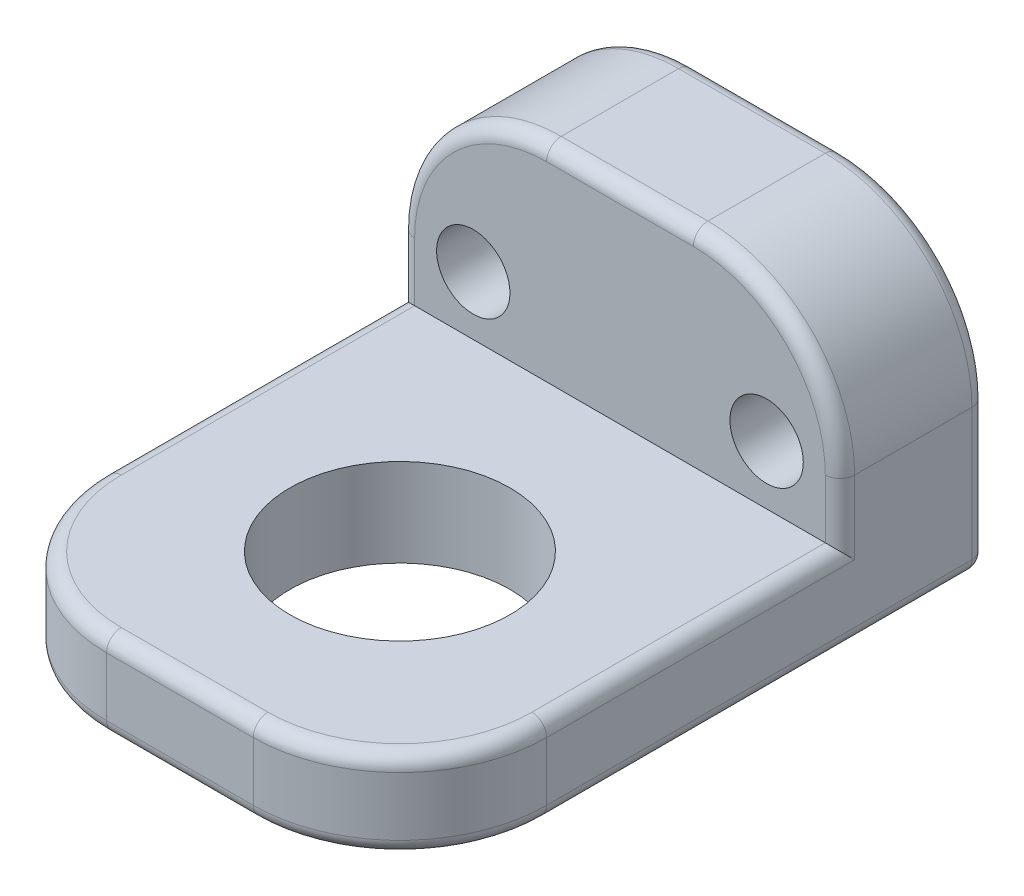
SolidWorks part; units mm, degrees
ref_plane "前视基准面" through (0, 0, 0) normal (0, 0, 1) x (1, 0, 0)
ref_plane "上视基准面" through (0, 0, 0) normal (0, 1, 0) x (1, 0, 0)
ref_plane "右视基准面" through (0, 0, 0) normal (1, 0, 0) x (0, 0, -1)
sketch "草图1" plane through (0, 0, 0) normal (0, 0, 1) x (1, 0, 0)
  line L1 (-15, 10) -> (15, 10)
  line L2 (-15, 10) -> (-15, -10)
  line L3 (-15, -10) -> (15, -10)
  line L4 (15, 10) -> (15, -10)
  line L5 (-15, 10) -> (15, -10) construction
  line L6 (-15, -10) -> (15, 10) construction
  point P0 (0, 0)
  dimension "D1" = 30
  dimension "D2" = 20
extrude "凸台-拉伸1" add sketch "草图1" along normal blind 10
sketch "草图2" plane through (0, 0, 10) normal (0, 0, 1) x (1, 0, 0)
  line L0 (-18.2315, 0) -> (18.886, 0) construction
  circle A0 centre (-10, 0) radius 2.5
  circle A1 centre (10, 0) radius 2.5
  dimension "D1" = 5
  dimension "D2" = 20
  dimension "D3" = 10
extrude "切除-拉伸1" cut sketch "草图2" against normal through all
sketch "草图3" plane through (0, 0, 10) normal (0, 0, 1) x (1, 0, 0)
  line L0 (-15, -10) -> (15, -10) construction
  line L2 (15, -10) -> (15, -4)
  line L3 (15, -4) -> (-15, -4)
  line L4 (-15, -10) -> (-15, -4)
  line L5 (0, -10) -> (-15, -4) construction
  line L6 (15, -4) -> (0, -10) construction
  line L7 (-15, 10) -> (-15, -10) construction
  line L8 (-15, -10) -> (15, -10)
  point P0 (0, -10)
  dimension "D1" = 6
extrude "凸台-拉伸2" add sketch "草图3" along normal blind 30
sketch "草图4" plane through (0, -10, 0) normal (0, -1, 0) x (1, 0, 0)
  line L0 (-15, 40) -> (15, 40) construction
  circle A0 centre (0, 25) radius 7.5
  dimension "D1" = 15
  dimension "D2" = 15
extrude "切除-拉伸2" cut sketch "草图4" against normal blind 30
fillet "圆角1" radius 10 2 edges at (-15, -7, 40) (15, -7, 40)
fillet "圆角2" radius 10 2 edges at (15, 10, 5) (-15, 10, 5)
fillet "圆角3" radius 1 11 edges at (15, -5, 0) (12.0711, 7.0711, 0) (0, 10, 0) (-12.0711, 7.0711, 0) (15, -10, 15) (12.0711, -10, 37.0711) (0, -10, 40) (-12.0711, -10, 37.0711) (-15, -5, 0) (0, -10, 0) (-15, -10, 15)
fillet "圆角4" radius 1 10 edges at (15, -4, 20) (12.0711, -4, 37.0711) (0, -4, 40) (-12.0711, -4, 37.0711) (15, -2, 10) (12.0711, 7.0711, 10) (0, 10, 10) (-15, -2, 10) (-15, -4, 20) (-12.0711, 7.0711, 10)
